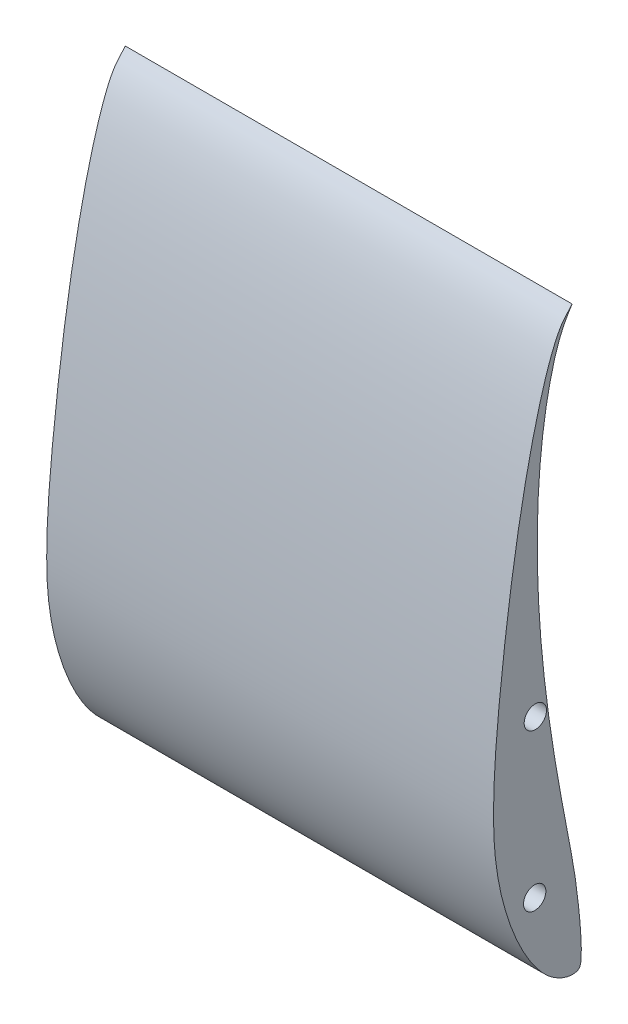
SolidWorks part; units mm, degrees
ref_plane "Front Plane" through (0, 0, 0) normal (0, 0, 1) x (1, 0, 0)
ref_plane "Top Plane" through (0, 0, 0) normal (0, 1, 0) x (1, 0, 0)
ref_plane "Right Plane" through (0, 0, 0) normal (1, 0, 0) x (0, 0, -1)
curve "Curve1"
  spline degree 3 poles (0, 258.9938, 0.6752) (0, 260.2357, -0.1678) (0, 259.1468, 0.6434) (0, 258.424, 1.3527) (0, 256.819, 2.8341) (0, 254.9254, 4.41) (0, 252.3352, 5.9987) (0, 249.1142, 7.5383) (0, 245.2258, 9.1451) (0, 240.6758, 10.7967) (0, 235.4854, 12.4814) (0, 229.6817, 14.1846) (0, 223.297, 15.8983) (0, 216.3667, 17.6067) (0, 208.9305, 19.2976) (0, 201.0327, 20.9603) (0, 192.7215, 22.5863) (0, 184.0456, 24.1555) (0, 175.0595, 25.6658) (0, 165.815, 27.0977) (0, 156.372, 28.454) (0, 146.7909, 29.7239) (0, 137.1411, 30.9034) (0, 127.4998, 32.0008) (0, 117.9468, 32.9884) (0, 108.5599, 33.8478) (0, 99.4052, 34.5306) (0, 90.5349, 35.0002) (0, 81.9984, 35.203) (0, 73.8394, 35.1815) (0, 66.0731, 34.782) (0, 58.6965, 33.9724) (0, 51.6797, 32.8277) (0, 45.0208, 31.3447) (0, 38.7268, 29.6058) (0, 32.8243, 27.6416) (0, 27.3383, 25.4981) (0, 22.303, 23.1868) (0, 17.7346, 20.7546) (0, 13.6578, 18.2293) (0, 10.0982, 15.6449) (0, 7.0573, 13.0563) (0, 4.5793, 10.4352) (0, 2.6758, 7.8044) (0, 1.2698, 5.2449) (0, 0.3686, 2.8149) (0, -0.0607, 0.5719) (0, 0.0221, -1.3251) (0, 0.5105, -3.065) (0, 2.326, -3.9287) (0, 4.7669, -4.0499) (0, 8.106, -4.1673) (0, 12.3052, -3.9862) (0, 17.3169, -3.6534) (0, 23.0855, -3.1204) (0, 29.5519, -2.3992) (0, 36.6846, -1.4744) (0, 44.48, -0.1818) (0, 52.9762, 1.4391) (0, 62.2156, 3.2032) (0, 72.153, 5.0658) (0, 82.7261, 6.9497) (0, 93.8571, 8.784) (0, 105.4597, 10.5077) (0, 117.434, 12.0573) (0, 129.6723, 13.3879) (0, 142.0589, 14.4397) (0, 154.4695, 15.1853) (0, 166.7745, 15.5952) (0, 178.8405, 15.647) (0, 190.5327, 15.3371) (0, 201.7173, 14.6728) (0, 212.2598, 13.6628) (0, 222.0347, 12.3457) (0, 230.9147, 10.7598) (0, 238.7957, 8.9582) (0, 245.5325, 7.0304) (0, 251.0459, 4.9728) (0, 254.9795, 3.0899) (0, 257.8797, 1.3489) (0, 258.9938, 0.6752) (0, 260.2357, -0.1678) (0, 259.1468, 0.6434) knots -0.009748 -0.004147 -0.001 0 0.00098 0.003649 0.007483 0.012095 0.017526 0.024052 0.031783 0.040678 0.05071 0.061833 0.073989 0.087118 0.101145 0.115991 0.13157 0.147788 0.164551 0.181758 0.199312 0.217095 0.23499 0.252857 0.270541 0.287887 0.304773 0.321101 0.336806 0.3518 0.366031 0.379616 0.392653 0.40517 0.417172 0.428604 0.439419 0.449597 0.459102 0.467908 0.475988 0.483309 0.489875 0.495803 0.501149 0.505903 0.510047 0.513579 0.516447 0.51935 0.523823 0.529974 0.537716 0.546968 0.557637 0.56962 0.582804 0.597247 0.613135 0.630444 0.649056 0.668822 0.689595 0.71119 0.733427 0.756094 0.778989 0.80189 0.824567 0.846792 0.868338 0.888978 0.908492 0.926659 0.943286 0.958169 0.971136 0.981956 0.990252 0.995853 0.999 1 1.00098 1.003649 1.007483 periodic
sketch "Sketch3" plane through (0, 0, 0) normal (1, 0, 0) x (0, 0, -1)
  circle A0 centre (-16.7409, 38.2319) radius 5
  circle A1 centre (-16.449, 108.2319) radius 5
  spline S0 degree 3 poles (-0.6752, 258.9938) (0.1678, 260.2357) (-0.6434, 259.1468) (-1.3527, 258.424) (-2.8341, 256.819) (-4.41, 254.9254) (-5.9987, 252.3352) (-7.5383, 249.1142) (-9.1451, 245.2258) (-10.7967, 240.6758) (-12.4814, 235.4854) (-14.1846, 229.6817) (-15.8983, 223.297) (-17.6067, 216.3667) (-19.2976, 208.9305) (-20.9603, 201.0327) (-22.5863, 192.7215) (-24.1555, 184.0456) (-25.6658, 175.0595) (-27.0977, 165.815) (-28.454, 156.372) (-29.7239, 146.7909) (-30.9034, 137.1411) (-32.0008, 127.4998) (-32.9884, 117.9468) (-33.8478, 108.5599) (-34.5306, 99.4052) (-35.0002, 90.5349) (-35.203, 81.9984) (-35.1815, 73.8394) (-34.782, 66.0731) (-33.9724, 58.6965) (-32.8277, 51.6797) (-31.3447, 45.0208) (-29.6058, 38.7268) (-27.6416, 32.8243) (-25.4981, 27.3383) (-23.1868, 22.303) (-20.7546, 17.7346) (-18.2293, 13.6578) (-15.6449, 10.0982) (-13.0563, 7.0573) (-10.4352, 4.5793) (-7.8044, 2.6758) (-5.2449, 1.2698) (-2.8149, 0.3686) (-0.5719, -0.0607) (1.3251, 0.0221) (3.065, 0.5105) (3.9287, 2.326) (4.0499, 4.7669) (4.1673, 8.106) (3.9862, 12.3052) (3.6534, 17.3169) (3.1204, 23.0855) (2.3992, 29.5519) (1.4744, 36.6846) (0.1818, 44.48) (-1.4391, 52.9762) (-3.2032, 62.2156) (-5.0658, 72.153) (-6.9497, 82.7261) (-8.784, 93.8571) (-10.5077, 105.4597) (-12.0573, 117.434) (-13.3879, 129.6723) (-14.4397, 142.0589) (-15.1853, 154.4695) (-15.5952, 166.7745) (-15.647, 178.8405) (-15.3371, 190.5327) (-14.6728, 201.7173) (-13.6628, 212.2598) (-12.3457, 222.0347) (-10.7598, 230.9147) (-8.9582, 238.7957) (-7.0304, 245.5325) (-4.9728, 251.0459) (-3.0899, 254.9795) (-1.3489, 257.8797) (-0.6752, 258.9938) (0.1678, 260.2357) (-0.6434, 259.1468) knots -0.009748 -0.004147 -0.001 0 0.00098 0.003649 0.007483 0.012095 0.017526 0.024052 0.031783 0.040678 0.05071 0.061833 0.073989 0.087118 0.101145 0.115991 0.13157 0.147788 0.164551 0.181758 0.199312 0.217095 0.23499 0.252857 0.270541 0.287887 0.304773 0.321101 0.336806 0.3518 0.366031 0.379616 0.392653 0.40517 0.417172 0.428604 0.439419 0.449597 0.459102 0.467908 0.475988 0.483309 0.489875 0.495803 0.501149 0.505903 0.510047 0.513579 0.516447 0.51935 0.523823 0.529974 0.537716 0.546968 0.557637 0.56962 0.582804 0.597247 0.613135 0.630444 0.649056 0.668822 0.689595 0.71119 0.733427 0.756094 0.778989 0.80189 0.824567 0.846792 0.868338 0.888978 0.908492 0.926659 0.943286 0.958169 0.971136 0.981956 0.990252 0.995853 0.999 1 1.00098 1.003649 1.007483 only from (0, 260) to (0, 260) construction
  spline S1 degree 3 poles (-0.6752, 258.9938) (0.1678, 260.2357) (-0.6434, 259.1468) (-1.3527, 258.424) (-2.8341, 256.819) (-4.41, 254.9254) (-5.9987, 252.3352) (-7.5383, 249.1142) (-9.1451, 245.2258) (-10.7967, 240.6758) (-12.4814, 235.4854) (-14.1846, 229.6817) (-15.8983, 223.297) (-17.6067, 216.3667) (-19.2976, 208.9305) (-20.9603, 201.0327) (-22.5863, 192.7215) (-24.1555, 184.0456) (-25.6658, 175.0595) (-27.0977, 165.815) (-28.454, 156.372) (-29.7239, 146.7909) (-30.9034, 137.1411) (-32.0008, 127.4998) (-32.9884, 117.9468) (-33.8478, 108.5599) (-34.5306, 99.4052) (-35.0002, 90.5349) (-35.203, 81.9984) (-35.1815, 73.8394) (-34.782, 66.0731) (-33.9724, 58.6965) (-32.8277, 51.6797) (-31.3447, 45.0208) (-29.6058, 38.7268) (-27.6416, 32.8243) (-25.4981, 27.3383) (-23.1868, 22.303) (-20.7546, 17.7346) (-18.2293, 13.6578) (-15.6449, 10.0982) (-13.0563, 7.0573) (-10.4352, 4.5793) (-7.8044, 2.6758) (-5.2449, 1.2698) (-2.8149, 0.3686) (-0.5719, -0.0607) (1.3251, 0.0221) (3.065, 0.5105) (3.9287, 2.326) (4.0499, 4.7669) (4.1673, 8.106) (3.9862, 12.3052) (3.6534, 17.3169) (3.1204, 23.0855) (2.3992, 29.5519) (1.4744, 36.6846) (0.1818, 44.48) (-1.4391, 52.9762) (-3.2032, 62.2156) (-5.0658, 72.153) (-6.9497, 82.7261) (-8.784, 93.8571) (-10.5077, 105.4597) (-12.0573, 117.434) (-13.3879, 129.6723) (-14.4397, 142.0589) (-15.1853, 154.4695) (-15.5952, 166.7745) (-15.647, 178.8405) (-15.3371, 190.5327) (-14.6728, 201.7173) (-13.6628, 212.2598) (-12.3457, 222.0347) (-10.7598, 230.9147) (-8.9582, 238.7957) (-7.0304, 245.5325) (-4.9728, 251.0459) (-3.0899, 254.9795) (-1.3489, 257.8797) (-0.6752, 258.9938) (0.1678, 260.2357) (-0.6434, 259.1468) knots -0.009748 -0.004147 -0.001 0 0.00098 0.003649 0.007483 0.012095 0.017526 0.024052 0.031783 0.040678 0.05071 0.061833 0.073989 0.087118 0.101145 0.115991 0.13157 0.147788 0.164551 0.181758 0.199312 0.217095 0.23499 0.252857 0.270541 0.287887 0.304773 0.321101 0.336806 0.3518 0.366031 0.379616 0.392653 0.40517 0.417172 0.428604 0.439419 0.449597 0.459102 0.467908 0.475988 0.483309 0.489875 0.495803 0.501149 0.505903 0.510047 0.513579 0.516447 0.51935 0.523823 0.529974 0.537716 0.546968 0.557637 0.56962 0.582804 0.597247 0.613135 0.630444 0.649056 0.668822 0.689595 0.71119 0.733427 0.756094 0.778989 0.80189 0.824567 0.846792 0.868338 0.888978 0.908492 0.926659 0.943286 0.958169 0.971136 0.981956 0.990252 0.995853 0.999 1 1.00098 1.003649 1.007483 only from (0, 260) to (0, 260)
  dimension "D2" = 10
  dimension "D3" = 10
  dimension "D1" = 70
extrude "Boss-Extrude2" add sketch "Sketch3" along normal blind 200
